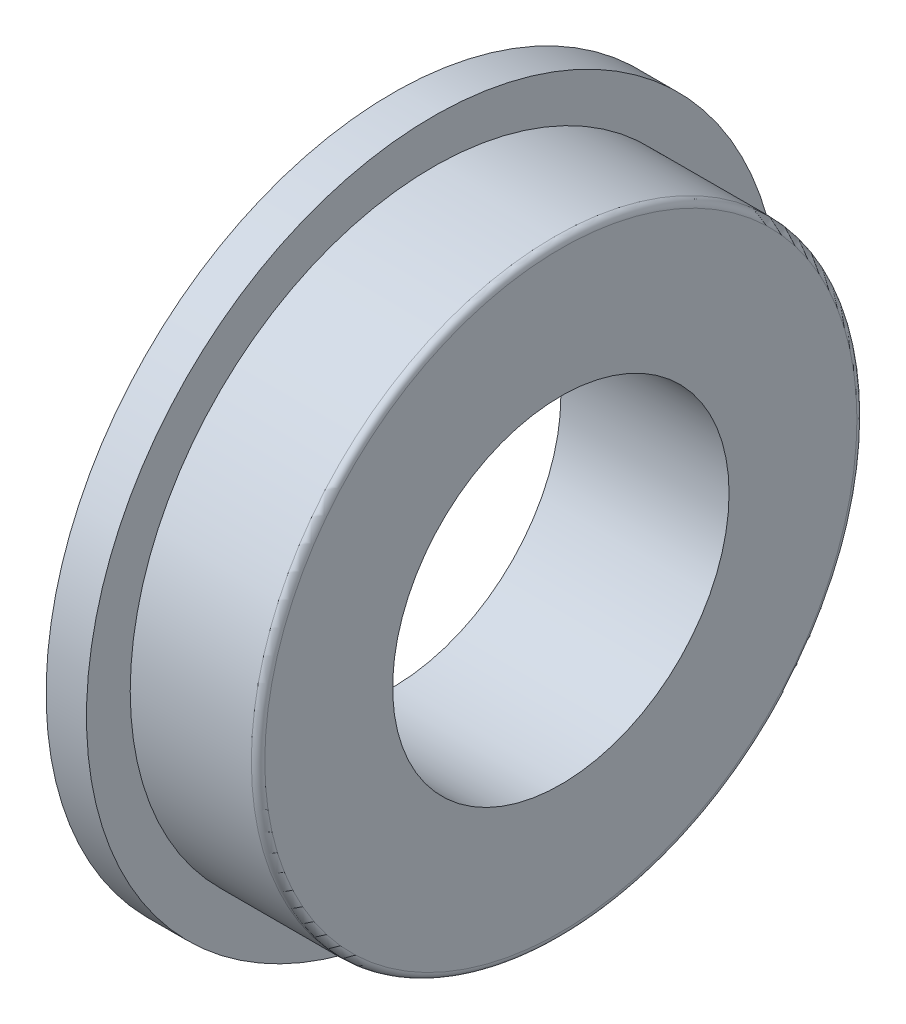
SolidWorks part; units mm, degrees
ref_plane "Front Plane" through (0, 0, 0) normal (0, 0, 1) x (1, 0, 0)
ref_plane "Top Plane" through (0, 0, 0) normal (0, 1, 0) x (1, 0, 0)
ref_plane "Right Plane" through (0, 0, 0) normal (1, 0, 0) x (0, 0, -1)
sketch "Sketch1" plane through (0, 0, 0) normal (1, 0, 0) x (0, 0, -1)
  circle A0 centre (0, 0) radius 5.15
  dimension "D1" = 10.3
extrude "Boss-Extrude1" add sketch "Sketch1" along normal blind 0.6
sketch "Sketch2" plane through (0.6, 0, 0) normal (1, 0, 0) x (0, 0, -1)
  circle A0 centre (0, 0) radius 4.5
  dimension "D1" = 9
extrude "Boss-Extrude2" add sketch "Sketch2" along normal blind 1.9
sketch "Sketch3" plane through (2.5, 0, 0) normal (1, 0, 0) x (0, 0, -1)
  circle A0 centre (0, 0) radius 2.5
  dimension "D1" = 5
extrude "Cut-Extrude1" cut sketch "Sketch3" against normal through all
fillet "Fillet1" radius 0.1 1 edges at (2.5, 0, -4.5)
